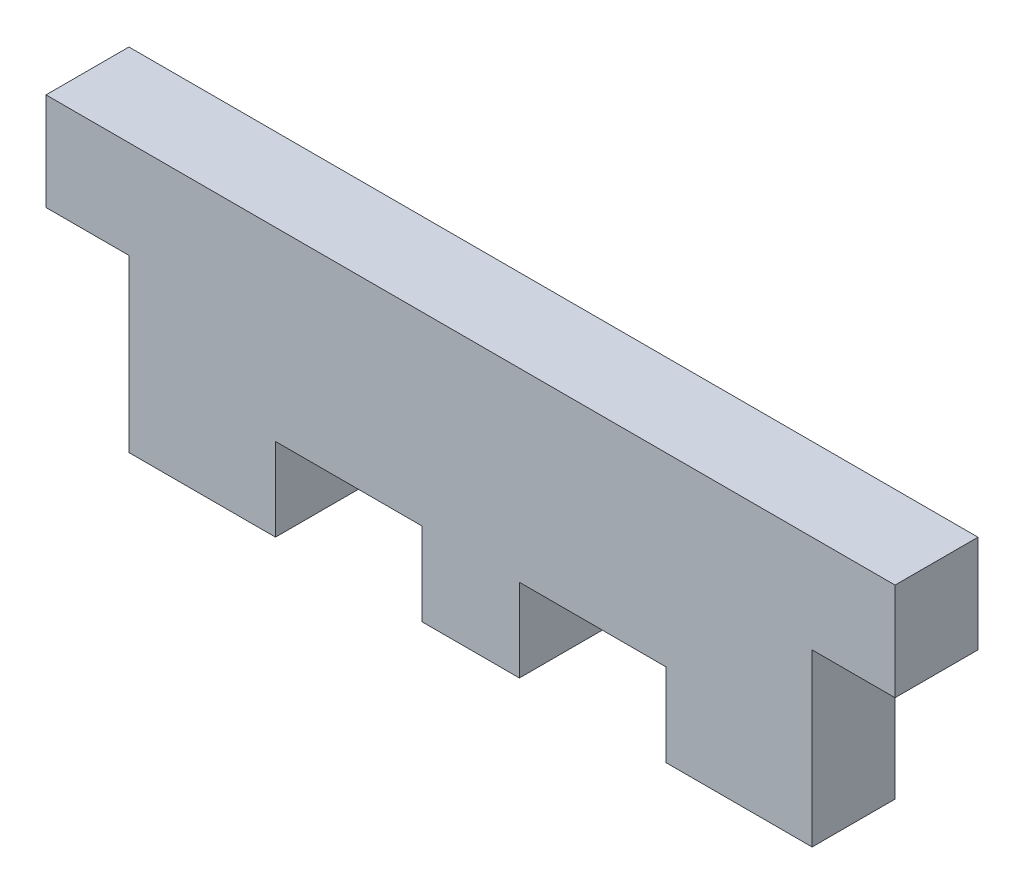
SolidWorks part; units mm, degrees
ref_plane "Front Plane" through (0, 0, 0) normal (0, 0, 1) x (1, 0, 0)
ref_plane "Top Plane" through (0, 0, 0) normal (0, 1, 0) x (1, 0, 0)
ref_plane "Right Plane" through (0, 0, 0) normal (1, 0, 0) x (0, 0, -1)
sketch "Sketch1" plane through (0, 0, 0) normal (0, 0, 1) x (1, 0, 0)
  line L0 (-70.0392, 27.5) -> (-87.0392, 27.5)
  line L1 (-70, -27.5) -> (-40, -27.5)
  line L2 (-87.0392, 27.5) -> (-87.0392, 7.5)
  line L3 (-70.0392, 27.5) -> (70, 27.5)
  line L4 (70, 27.5) -> (87, 27.5)
  line L5 (-40, -10.5) -> (-40, -27.5)
  line L6 (-40, -10.5) -> (-10, -10.5)
  line L7 (-10, -10.5) -> (-10, -27.5)
  line L8 (-87.0392, 7.5) -> (-70.0392, 7.5)
  line L9 (10, -10.5) -> (10, -27.5)
  line L10 (10, -10.5) -> (40, -10.5)
  line L11 (40, -10.5) -> (40, -27.5)
  line L12 (-70.0392, 7.5) -> (-70.0392, -7.5)
  line L13 (-10, -27.5) -> (10, -27.5)
  line L14 (40, -27.5) -> (70, -27.5)
  line L18 (87, 27.5) -> (87, 7.5)
  line L19 (87, 7.5) -> (70, 7.5)
  line L20 (70, 7.5) -> (70, -7.5)
  line L24 (-70.0392, -7.5) -> (-70, -27.5)
  line L25 (70, -7.5) -> (70, -27.5)
  point P0 (0, 0)
  dimension "D1" = 140
  dimension "D2" = 55
  dimension "D3" = 17
  dimension "D4" = 20
  dimension "D5" = 30
  dimension "D6" = 20
  dimension "D7" = 30
  dimension "D8" = 15
  dimension "D9" = 17
extrude "Boss-Extrude1" add sketch "Sketch1" along normal blind 17
